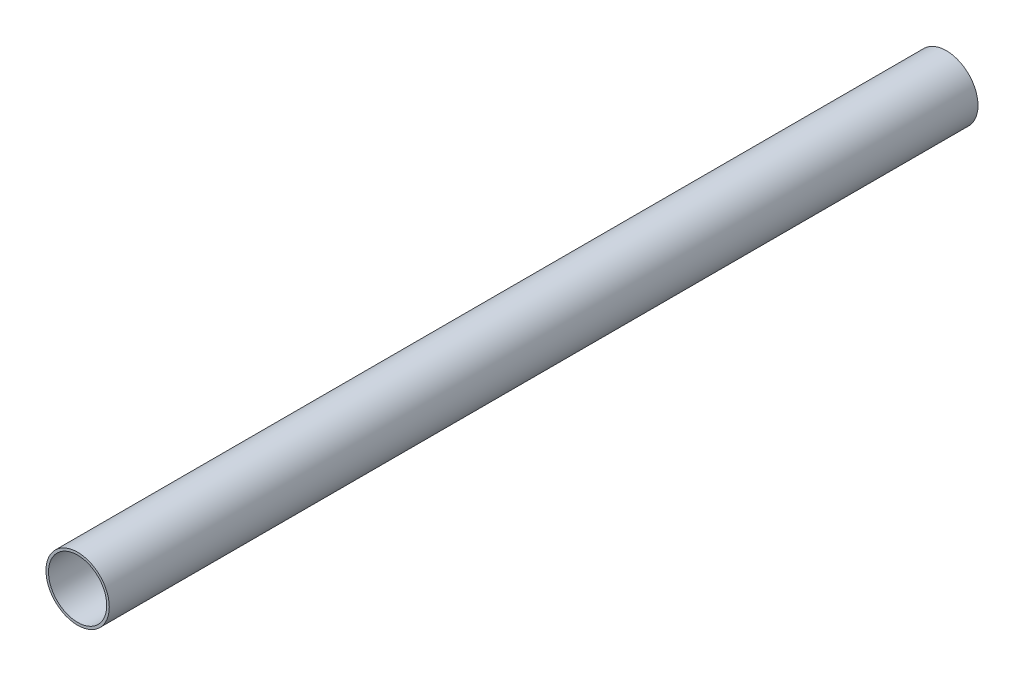
SolidWorks part; units mm, degrees
ref_plane "Front Plane" through (0, 0, 0) normal (0, 0, 1) x (1, 0, 0)
ref_plane "Top Plane" through (0, 0, 0) normal (0, 1, 0) x (1, 0, 0)
ref_plane "Right Plane" through (0, 0, 0) normal (1, 0, 0) x (0, 0, -1)
sketch "Sketch1" plane through (0, 0, 0) normal (0, 0, 1) x (1, 0, 0)
  line L0 (11.1125, 0) -> (10.2235, 0) construction
  line L1 (-11.1125, 0) -> (11.1125, 0) construction
  dimension "OD" = 22.225
  dimension "Wall Thickness" = 0.889
sketch "Sketch2" plane through (0, 0, 0) normal (1, 0, 0) x (0, 0, -1)
  line L0 (152.4, 0) -> (-152.4, 0)
  point P4 (0, 0)
  dimension "Length" = 304.8
sketch "Sketch3" plane through (0, 0, 0) normal (0, 0, 1) x (1, 0, 0)
  circle A0 centre (0, 0) radius 11.1125
  circle A1 centre (0, 0) radius 10.2235
extrude "Boss-Extrude1" add sketch "Sketch3" along normal up to vertex (152.4 mm away) and the other way up to vertex (152.4 mm away) up to point (0, 0, 152.4) other way up to point (0, 0, -152.4)
